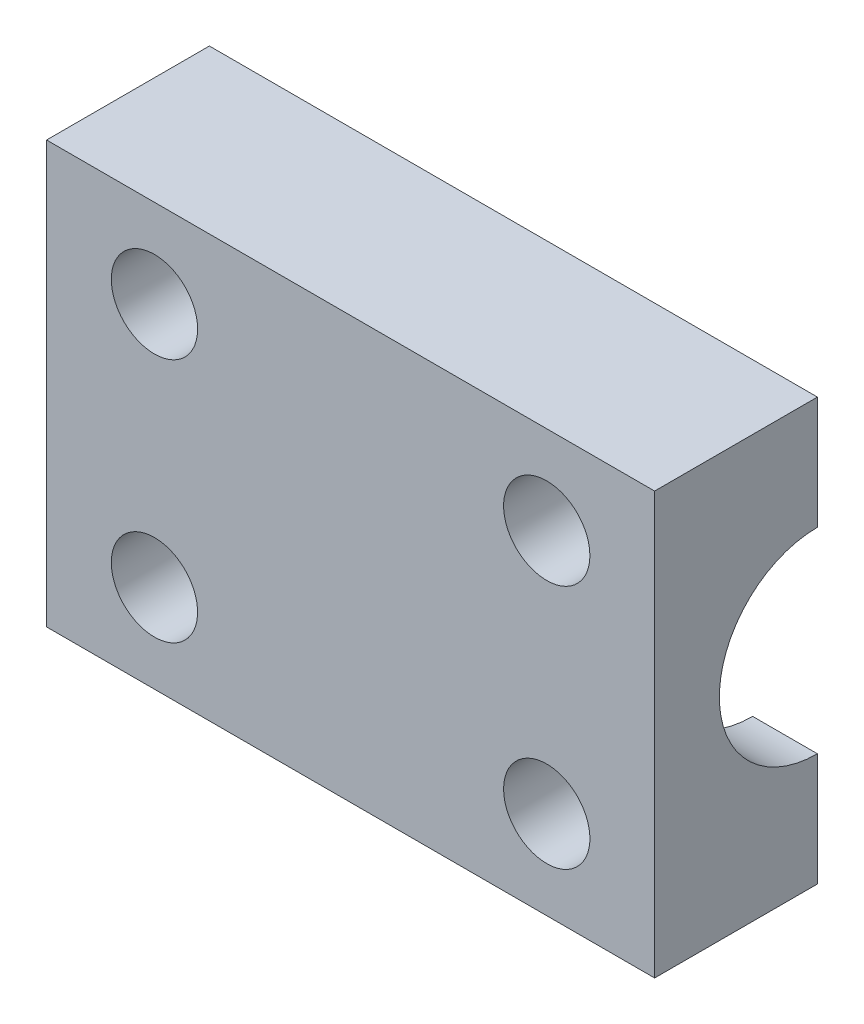
SolidWorks part; units mm, degrees
ref_plane "Front Plane" through (0, 0, 0) normal (0, 0, 1) x (1, 0, 0)
ref_plane "Top Plane" through (0, 0, 0) normal (0, 1, 0) x (1, 0, 0)
ref_plane "Right Plane" through (0, 0, 0) normal (1, 0, 0) x (0, 0, -1)
ref_plane "Plane1" through (0, 0, -8.3) normal (0, 0, -1) x (-1, 0, 0)
sketch "Sketch1" plane through (0, 0, -8.3) normal (0, 0, -1) x (-1, 0, 0)
  line L0 (-18, 10.75) -> (-18, -10.75)
  line L1 (-18, -10.75) -> (13, -10.75)
  line L2 (13, -10.75) -> (13, 10.75)
  line L3 (13, 10.75) -> (-18, 10.75)
extrude "Boss-Extrude1" add sketch "Sketch1" against normal blind 8.3
ref_plane "Plane2" through (5.7, 0, 0) normal (1, 0, 0) x (0, 0, -1)
sketch "Sketch2" plane through (5.7, 0, 0) normal (1, 0, 0) x (0, 0, -1)
  line L0 (8.3, -7.5232) -> (8.3, 7.5232)
  line L1 (8.3, 7.5232) -> (1.8347, 3.7905)
  line L2 (1.8347, 3.7905) -> (1.8347, -3.7905)
  line L3 (1.8347, -3.7905) -> (8.3, -7.5232)
extrude "Cut-Extrude1" cut sketch "Sketch2" against normal blind 6.4
sketch "Sketch3" plane through (0, 0, -8.3) normal (0, 0, -1) x (-1, 0, 0)
  line L0 (-14.7, 6.25) -> (-14.7, -6.25)
  line L1 (-10.3, -6.25) -> (-10.3, 6.25)
  arc A0 (-14.7, -6.25) -> (-10.3, -6.25) centre (-12.5, -6.25) cw
  arc A1 (-10.3, 6.25) -> (-14.7, 6.25) centre (-12.5, 6.25) cw
extrude "Cut-Extrude2" cut sketch "Sketch3" against normal blind 3.5
sketch "Sketch4" plane through (0, 0, -8.3) normal (0, 0, -1) x (-1, 0, 0)
  line L0 (5.3, 6.25) -> (5.3, -6.25)
  line L1 (9.7, -6.25) -> (9.7, 6.25)
  arc A0 (5.3, -6.25) -> (9.7, -6.25) centre (7.5, -6.25) cw
  arc A1 (9.7, 6.25) -> (5.3, 6.25) centre (7.5, 6.25) cw
extrude "Cut-Extrude3" cut sketch "Sketch4" against normal blind 3.5
ref_plane "Plane3" through (0, 6.25, 0) normal (0, 1, 0) x (-1, 0, 0)
sketch "Sketch5" plane through (0, 6.25, 0) normal (0, 1, 0) x (-1, 0, 0)
  line L0 (5.3, -8.3) -> (7.5, -8.3)
  line L1 (7.5, -8.3) -> (7.5, 0)
  line L2 (7.5, 0) -> (5.3, 0)
  line L3 (5.3, 0) -> (5.3, -8.3)
  line L4 (7.5, -8.3) -> (7.5, 0) construction
revolve "Cut-Revolve1" cut sketch "Sketch5" angle 360 about L4
sketch "Sketch6" plane through (0, 6.25, 0) normal (0, 1, 0) x (-1, 0, 0)
  line L0 (-14.7, -8.3) -> (-12.5, -8.3)
  line L1 (-12.5, -8.3) -> (-12.5, 0)
  line L2 (-12.5, 0) -> (-14.7, 0)
  line L3 (-14.7, 0) -> (-14.7, -8.3)
  line L4 (-12.5, -8.3) -> (-12.5, 0) construction
revolve "Cut-Revolve2" cut sketch "Sketch6" angle 360 about L4
ref_plane "Plane4" through (0, -6.25, 0) normal (0, -1, 0) x (1, 0, 0)
sketch "Sketch7" plane through (0, -6.25, 0) normal (0, -1, 0) x (1, 0, 0)
  line L0 (14.7, 0) -> (12.5, 0)
  line L1 (12.5, 0) -> (12.5, -8.3)
  line L2 (12.5, -8.3) -> (14.7, -8.3)
  line L3 (14.7, -8.3) -> (14.7, 0)
  line L4 (12.5, 0) -> (12.5, -8.3) construction
revolve "Cut-Revolve3" cut sketch "Sketch7" angle 360 about L4
sketch "Sketch8" plane through (0, -6.25, 0) normal (0, -1, 0) x (1, 0, 0)
  line L0 (-5.3, 0) -> (-7.5, 0)
  line L1 (-7.5, 0) -> (-7.5, -8.3)
  line L2 (-7.5, -8.3) -> (-5.3, -8.3)
  line L3 (-5.3, -8.3) -> (-5.3, 0)
  line L4 (-7.5, 0) -> (-7.5, -8.3) construction
revolve "Cut-Revolve4" cut sketch "Sketch8" angle 360 about L4
hole_wizard "Hole1" positions "Sketch10" profile "Sketch9" legacy
sketch "Sketch10" plane through (5.7, 0, 0) normal (-1, 0, 0) x (0, 0, 1)
  point P0 (-8.3, 0)
sketch "Sketch9" plane through (5.7, 0, -8.3) normal (0, 1, 0) x (0, 0, 1)
  line L0 (0, 0) -> (0, 12.3)
  line L1 (0, 12.3) -> (5, 12.3)
  line L2 (5, 12.3) -> (5, 0)
  line L3 (5, 0) -> (0, 0)
  line L4 (0, 110) -> (0, -10) construction
  dimension "Diameter" = 10
  dimension "Depth" = 12.3
hole_wizard "Hole2" positions "Sketch12" profile "Sketch11" legacy
sketch "Sketch12" plane through (-13, 0, 0) normal (-1, 0, 0) x (0, 0, 1)
  point P0 (-8.3, 0)
sketch "Sketch11" plane through (-13, 0, -8.3) normal (0, 1, 0) x (0, 0, 1)
  line L0 (0, 0) -> (0, 31)
  line L1 (0, 31) -> (5, 31)
  line L2 (5, 31) -> (5, 0)
  line L3 (5, 0) -> (0, 0)
  line L4 (0, 110) -> (0, -10) construction
  dimension "Diameter" = 10
  dimension "Depth" = 31
